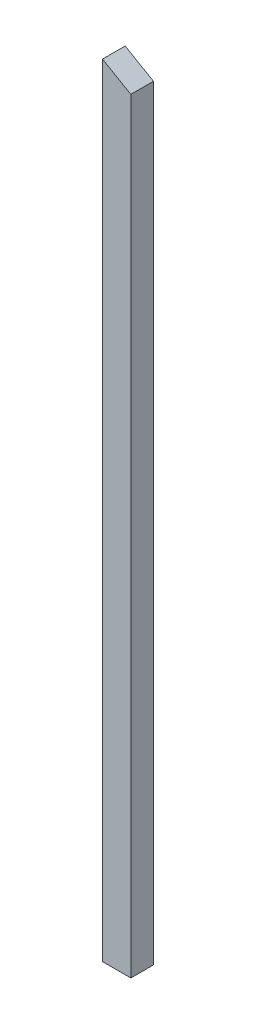
SolidWorks part; units mm, degrees
ref_plane "Plan de face" through (0, 0, 0) normal (0, 0, 1) x (1, 0, 0)
ref_plane "Plan de dessus" through (0, 0, 0) normal (0, 1, 0) x (1, 0, 0)
ref_plane "Plan de droite" through (0, 0, 0) normal (1, 0, 0) x (0, 0, -1)
sketch "Esquisse1" plane through (0, 0, 0) normal (0, 0, 1) x (1, 0, 0)
  line L1 (0, 0) -> (50, 0)
  line L2 (0, 0) -> (0, 1350)
  line L3 (0, 1350) -> (50, 1350)
  line L4 (50, 0) -> (50, 1350)
  dimension "D1" = 50
  dimension "D2" = 1350
extrude "Boss.-Extru.1" add sketch "Esquisse1" along normal blind 40
sketch "Esquisse2" plane through (0, 0, 40) normal (0, 0, 1) x (1, 0, 0)
  line L0 (50, 1350) -> (0, 1350)
  line L1 (0, 1350) -> (0, 1378.8675)
  line L2 (0, 1378.8675) -> (50, 1350)
  dimension "D1" = 30
extrude "Boss.-Extru.2" add sketch "Esquisse2" against normal up to vertex (40 mm away)
